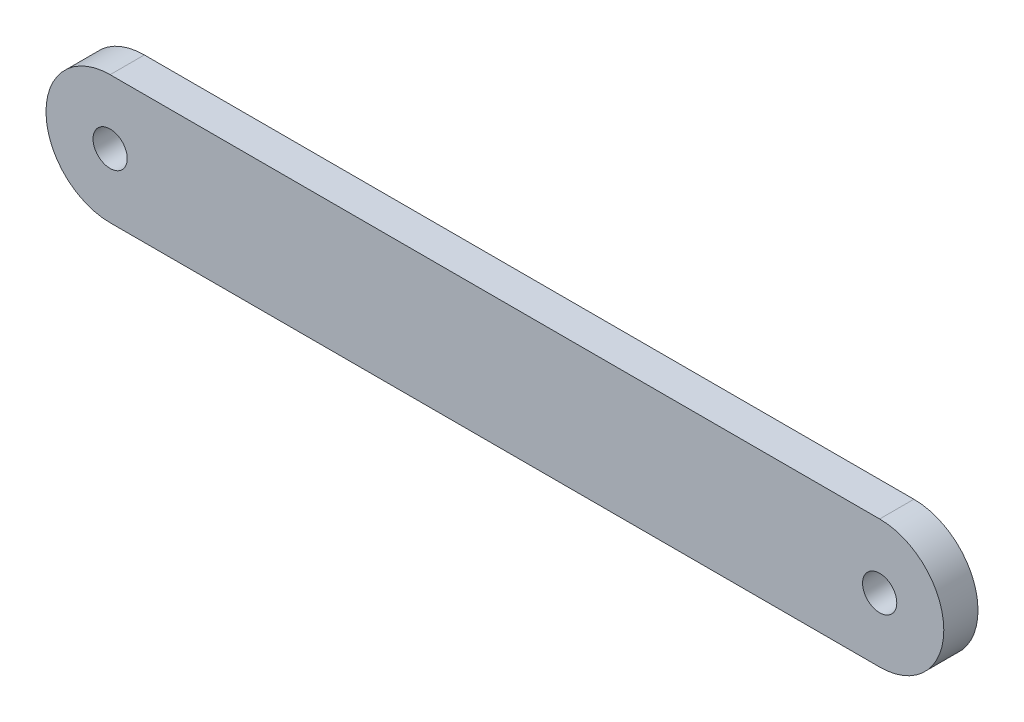
SolidWorks part; units mm, degrees
material "Pine"
ref_plane "Front Plane" through (0, 0, 0) normal (0, 0, 1) x (1, 0, 0)
ref_plane "Top Plane" through (0, 0, 0) normal (0, 1, 0) x (1, 0, 0)
ref_plane "Right Plane" through (0, 0, 0) normal (1, 0, 0) x (0, 0, -1)
sketch "Sketch1" plane through (0, 0, 0) normal (0, 0, 1) x (1, 0, 0)
  line L0 (0, 0) -> (90, 0) construction
  line L1 (0, 7.5) -> (90, 7.5)
  line L2 (0, -7.5) -> (90, -7.5)
  arc A0 (0, 7.5) -> (0, -7.5) centre (0, 0) ccw
  arc A1 (90, -7.5) -> (90, 7.5) centre (90, 0) ccw
  circle A2 centre (0, 0) radius 2
  circle A3 centre (90, 0) radius 2
  circle A4 centre (40, 0) radius 2
  point P3 (45, 0)
  dimension "D1" = 4
  dimension "D4" = 50
  dimension "D2" = 15
  dimension "D3" = 90
extrude "Boss-Extrude1" add sketch "Sketch1" along normal blind 4
